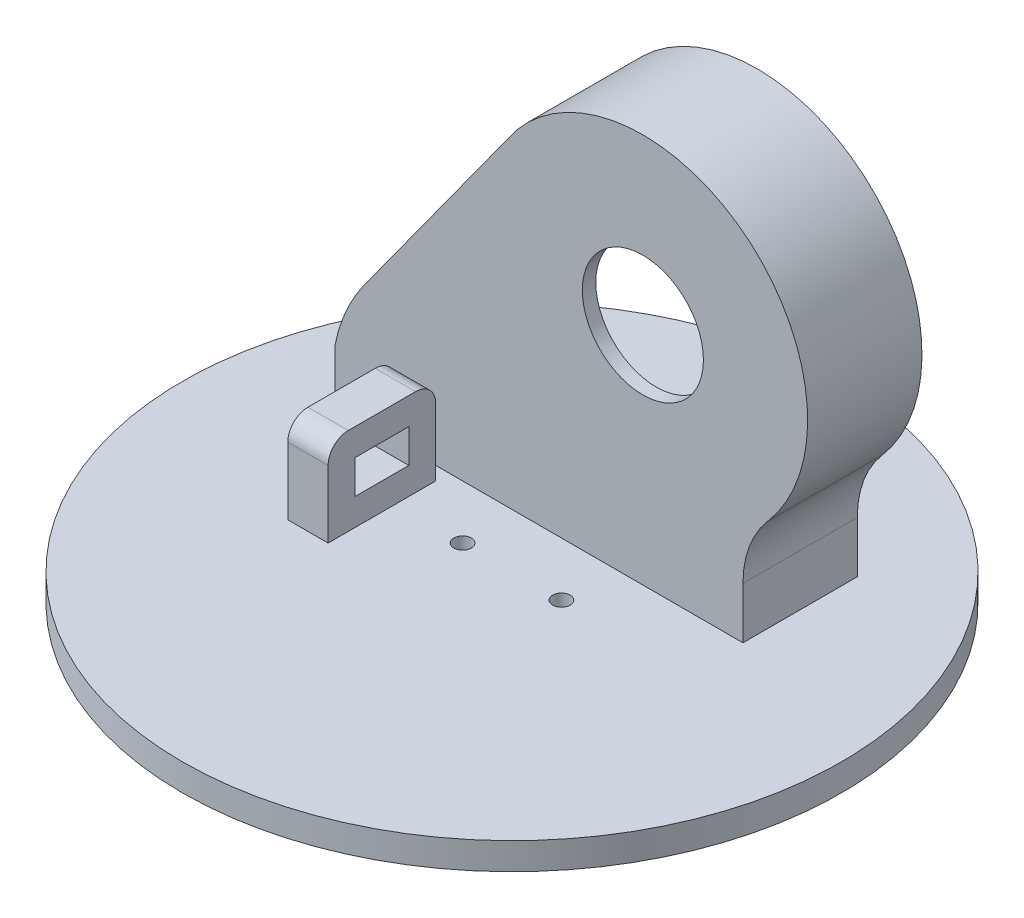
SolidWorks part; units mm, degrees
ref_plane "Front Plane" through (0, 0, 0) normal (0, 0, 1) x (1, 0, 0)
ref_plane "Top Plane" through (0, 0, 0) normal (0, 1, 0) x (1, 0, 0)
ref_plane "Right Plane" through (0, 0, 0) normal (1, 0, 0) x (0, 0, -1)
sketch "Sketch2" plane through (0, 0, 0) normal (0, 0, 1) x (1, 0, 0)
  line L0 (14.8818, -33.4772) -> (14.8818, -25.8326)
  line L2 (-18.7505, 15.7691) -> (-41.4957, -15.6593)
  line L3 (-45.7977, -25.6186) -> (-45.7977, -33.4772)
  line L4 (-45.7977, -33.4772) -> (14.8818, -33.4772)
  arc A0 (18.5343, -16.0227) -> (-18.7505, 15.7691) centre (0, 0) ccw
  circle A1 centre (0, 0) radius 9
  arc A2 (-41.4957, -15.6593) -> (-45.7977, -25.6186) centre (-21.2435, -30.3162) ccw
  arc A3 (18.5343, -16.0227) -> (14.8818, -25.8326) centre (29.8818, -25.8326) ccw
  dimension "D1" = 15
  dimension "D2" = 18
  dimension "D3" = 24.4999
  dimension "D8" = 24.9995
  dimension "D4" = 38.7954
  dimension "D5" = 60.6795
  dimension "D6" = 7.8586
  dimension "D7" = 7.6446
  dimension "D9" = 10.8488
  dimension "D10" = 10.4678
extrude "Boss-Extrude1" add sketch "Sketch2" along normal blind 17
sketch "Sketch4" plane through (0, 0, 0) normal (0, 0, -1) x (-1, 0, 0)
  line L4 (-11.8818, -30.4772) -> (-11.8818, -33.4772)
  line L5 (45.7977, -33.4772) -> (-14.8818, -33.4772) construction
  line L6 (-11.8818, -33.4772) -> (42.7977, -33.4772)
  line L7 (42.7977, -33.4772) -> (42.7977, -30.4772)
  line L8 (-11.8818, -30.4772) -> (42.7977, -30.4772)
  line L9 (42.7977, -30.4772) -> (42.7977, -25.9122)
  line L10 (39.0654, -17.4181) -> (16.3864, 13.9188)
  line L11 (-11.8818, -25.8326) -> (-11.8818, -30.4772)
  line L13 (42.7977, -30.4772) -> (42.7977, -25.9122)
  line L14 (39.0654, -17.4181) -> (16.3864, 13.9188)
  line L15 (-11.8818, -25.8326) -> (-11.8818, -30.4772)
  arc A6 (42.7977, -25.9122) -> (39.0654, -17.4181) centre (21.2435, -30.3162) ccw
  arc A7 (16.3864, 13.9188) -> (-16.2647, -14.0608) centre (0, 0) ccw
  arc A8 (-11.8818, -25.8326) -> (-16.2647, -14.0608) centre (-29.8818, -25.8326) ccw
  arc A9 (42.7977, -25.9122) -> (39.0654, -17.4181) centre (21.2435, -30.3162) ccw
  arc A10 (16.3864, 13.9188) -> (-16.2647, -14.0608) centre (0, 0) ccw
  arc A11 (-11.8818, -25.8326) -> (-16.2647, -14.0608) centre (-29.8818, -25.8326) ccw
  dimension "D1" = 3
extrude "Cut-Extrude1" cut sketch "Sketch4" against normal blind 4
sketch "Sketch5" plane through (0, 0, 4) normal (0, 0, -1) x (-1, 0, 0)
  line L0 (0, 0) -> (6.364, 6.364) construction
  line L1 (0, 0) -> (9, 0) construction
  line L2 (0, 0) -> (-7.7782, 7.7782) construction
  line L4 (-14.8492, 0.7071) -> (-0.7071, 14.8492)
  line L6 (-0.7071, 14.8492) -> (27.5772, -13.435)
  line L7 (27.5772, -13.435) -> (13.435, -27.5772)
  line L8 (13.435, -27.5772) -> (-14.8492, 0.7071)
  circle A0 centre (0, 0) radius 9 construction
  circle A1 centre (0, 0) radius 9
  point P11 (-7.7782, 7.7782)
  dimension "D1" = 45
  dimension "D2" = 90
  dimension "D3" = 11
  dimension "D4" = 90
  dimension "D5" = 20
  dimension "D6" = 20
  dimension "D7" = 40
extrude "Cut-Extrude3" cut sketch "Sketch5" against normal blind 11
sketch "Sketch7" plane through (0, 0, 4) normal (0, 0, -1) x (-1, 0, 0)
  line L0 (-0.7071, 14.8492) -> (-14.8492, 0.7071) construction
  line L1 (-6.5902, 15.3301) -> (-14.5805, 7.3398) construction
  line L3 (13.435, 0.7071) -> (-0.7071, -13.435) construction
  line L4 (27.5772, -13.435) -> (-0.7071, 14.8492) construction
  line L5 (-14.8492, 0.7071) -> (13.435, -27.5772) construction
  line L6 (23.6881, -23.6881) -> (20.5061, -20.5061) construction
  line L7 (28.058, -19.3182) -> (20.0677, -27.3085) construction
  line L8 (27.5772, -13.435) -> (13.435, -27.5772) construction
  line L9 (-0.7071, 14.8492) -> (-6.0104, 20.1525) construction
  line L10 (-6.0104, 20.1525) -> (-21.2466, 4.9163) construction
  circle A0 centre (-6.5902, 15.3301) radius 2.15
  circle A1 centre (-14.5805, 7.3398) radius 2.15
  circle A2 centre (20.0677, -27.3085) radius 2.15
  circle A3 centre (28.058, -19.3182) radius 2.15
  dimension "D3" = 4.3
  dimension "D4" = 4.3
  dimension "D5" = 27.5
  dimension "D1" = 3
  dimension "D2" = 11.3
  dimension "D6" = 3.82
extrude "Cut-Extrude4" cut sketch "Sketch7" against normal blind 7
sketch "Sketch8" plane through (0, -33.4772, 0) normal (0, -1, 0) x (1, 0, 0)
  line L0 (-45.7977, 17) -> (14.8818, 17) construction
  line L1 (-15.458, 17) -> (-11.458, 17) construction
  line L2 (-11.458, 17) -> (-11.458, 25) construction
  line L3 (-4.108, 25) -> (-18.808, 25) construction
  circle A0 centre (-18.808, 25) radius 1.3
  circle A1 centre (-4.108, 25) radius 1.3
  circle A2 centre (-11.458, 25) radius 49
  point P10 (-11.458, 25)
  dimension "D4" = 2.6
  dimension "D5" = 2.6
  dimension "D6" = 98
  dimension "D1" = 4
  dimension "D2" = 8
  dimension "D3" = 14.7
extrude "Boss-Extrude2" add sketch "Sketch8" along normal blind 4
sketch "Sketch9" plane through (0, -33.4772, 0) normal (0, 1, 0) x (1, 0, 0)
  line L0 (-45.7977, -17) -> (24.4999, -17) construction
  line L1 (-45.7977, -19) -> (24.4999, -19) construction
  line L2 (-45.7977, -17) -> (-45.7977, -35) construction
  line L3 (-34.7977, -17) -> (-34.7977, -35) construction
  line L4 (-34.7977, -35) -> (-28.7977, -35)
  line L5 (-28.7977, -35) -> (-28.7977, -19)
  line L6 (-28.7977, -19) -> (-34.7977, -19)
  line L7 (-34.7977, -19) -> (-34.7977, -35)
  dimension "D2" = 2
  dimension "D4" = 11
  dimension "D5" = 18
  dimension "D6" = 6
  dimension "D1" = 2
  dimension "D3" = 2
extrude "Boss-Extrude3" add sketch "Sketch9" along normal blind 13
fillet "Fillet1" radius 3 2 edges at (-31.7977, -20.4772, 19) (-31.7977, -20.4772, 35)
sketch "Sketch10" plane through (-34.7977, 0, 0) normal (-1, 0, 0) x (0, 0, 1)
  line L8 (31, -24.4772) -> (23, -24.4772)
  line L9 (23, -24.4772) -> (23, -29.4772)
  line L10 (23, -29.4772) -> (31, -29.4772)
  line L11 (31, -29.4772) -> (31, -24.4772)
  line L12 (31, -24.4772) -> (23, -24.4772)
  line L13 (23, -24.4772) -> (23, -29.4772)
  line L14 (23, -29.4772) -> (31, -29.4772)
  line L15 (31, -29.4772) -> (31, -24.4772)
  dimension "D1" = 4
extrude "Cut-Extrude5" cut sketch "Sketch10" against normal blind 13
ref_point "Point1"
ref_point "Point2"
